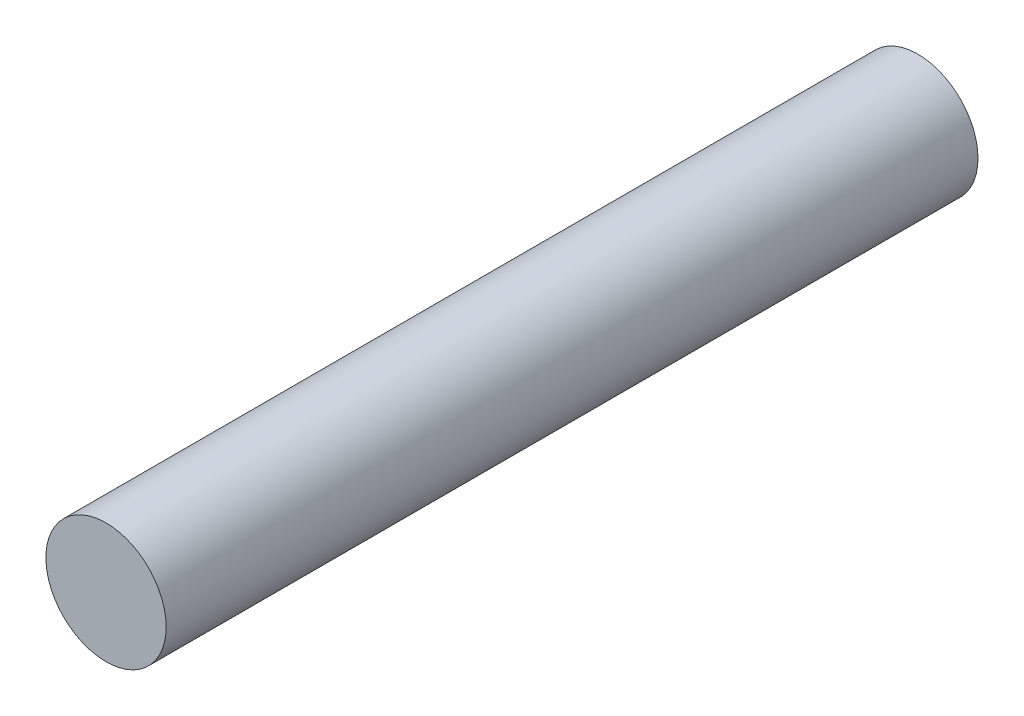
SolidWorks part; units mm, degrees
ref_plane "Front Plane" through (0, 0, 0) normal (0, 0, 1) x (1, 0, 0)
ref_plane "Top Plane" through (0, 0, 0) normal (0, 1, 0) x (1, 0, 0)
ref_plane "Right Plane" through (0, 0, 0) normal (1, 0, 0) x (0, 0, -1)
sketch "Sketch1" plane through (0, 0, 0) normal (0, 0, 1) x (1, 0, 0)
  circle A0 centre (0, 0) radius 2
  dimension "D1" = 4
extrude "Boss-Extrude1" add sketch "Sketch1" along normal blind 27
